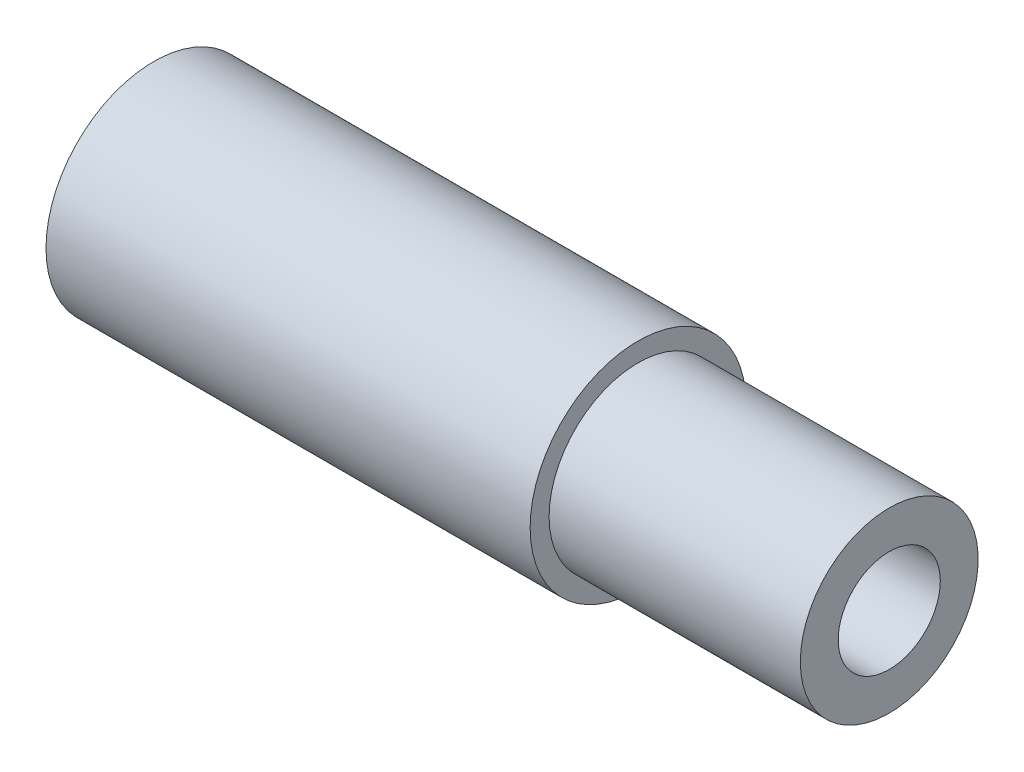
SolidWorks part; units mm, degrees
material "AISI 304"
ref_plane "Front Plane" through (0, 0, 0) normal (0, 0, 1) x (1, 0, 0)
ref_plane "Top Plane" through (0, 0, 0) normal (0, 1, 0) x (1, 0, 0)
ref_plane "Right Plane" through (0, 0, 0) normal (1, 0, 0) x (0, 0, -1)
sketch "Sketch1" plane through (0, 0, 0) normal (0, 0, 1) x (1, 0, 0)
  line L0 (0, 0) -> (50000, 0) construction
  line L1 (0, 0) -> (0, -2.3876)
  line L4 (0, -2.3876) -> (10.7188, -2.3876)
  line L5 (10.7188, -2.3876) -> (10.7188, -1.9685)
  line L6 (10.7188, -1.9685) -> (16.2814, -1.9685)
  line L7 (16.2814, -1.9685) -> (16.2814, 0)
  line L8 (0, 0) -> (16.2814, 0)
  dimension "D2" = 4.7752
  dimension "D4" = 5.5626
  dimension "D5" = 16.2814
revolve "Revolve1" add sketch "Sketch1" angle 360 about L0
hole_wizard "#4-40 Tapped Hole1" [suppressed] positions "Sketch4" profile "Sketch3" tap size "#4-40" standard "ANSI Inch"
sketch "Sketch4" plane through (0, 0, 0) normal (-1, 0, 0) x (0, 0, 1)
  point P0 (0, 0)
sketch "Sketch3" plane through (0, 0, 0) normal (0, 1, 0) x (0, 0, 1)
  line L0 (0, 0) -> (0, 8.2992)
  line L1 (0, 8.2992) -> (1.1303, 7.62)
  line L2 (1.1303, 7.62) -> (1.1303, 0)
  line L5 (1.1303, 0) -> (0, 0)
  line L10 (0, 8.2992) -> (-1.1303, 7.62) construction
  line L11 (0, -6.35) -> (0, 107.95) construction
  dimension "Tap Drill Dia." = 2.2606
  dimension "Tap Drill Depth" = 7.62
  dimension "Drill Angle" = 118
cosmetic thread "Hole Thread1" [suppressed] parameters "D1"=5.588, "D2"=2.8448
hole_wizard "#4-40 Tapped Hole2" positions "Sketch6" profile "Sketch5" tap size "#4-40" standard "ANSI Inch"
sketch "Sketch6" plane through (16.2814, 0, 0) normal (1, 0, 0) x (0, 0, -1)
  point P0 (0, 0)
sketch "Sketch5" plane through (16.2814, 0, 0) normal (0, 1, 0) x (0, 0, -1)
  line L0 (0, 0) -> (0, 5.7592)
  line L1 (0, 5.7592) -> (1.1303, 5.08)
  line L2 (1.1303, 5.08) -> (1.1303, 0)
  line L5 (1.1303, 0) -> (0, 0)
  line L10 (0, 5.7592) -> (-1.1303, 5.08) construction
  line L11 (0, -6.35) -> (0, 107.95) construction
  dimension "Tap Drill Dia." = 2.2606
  dimension "Tap Drill Depth" = 5.08
  dimension "Drill Angle" = 118
cosmetic thread "Hole Thread2" parameters "D1"=3.81, "D2"=2.8448
